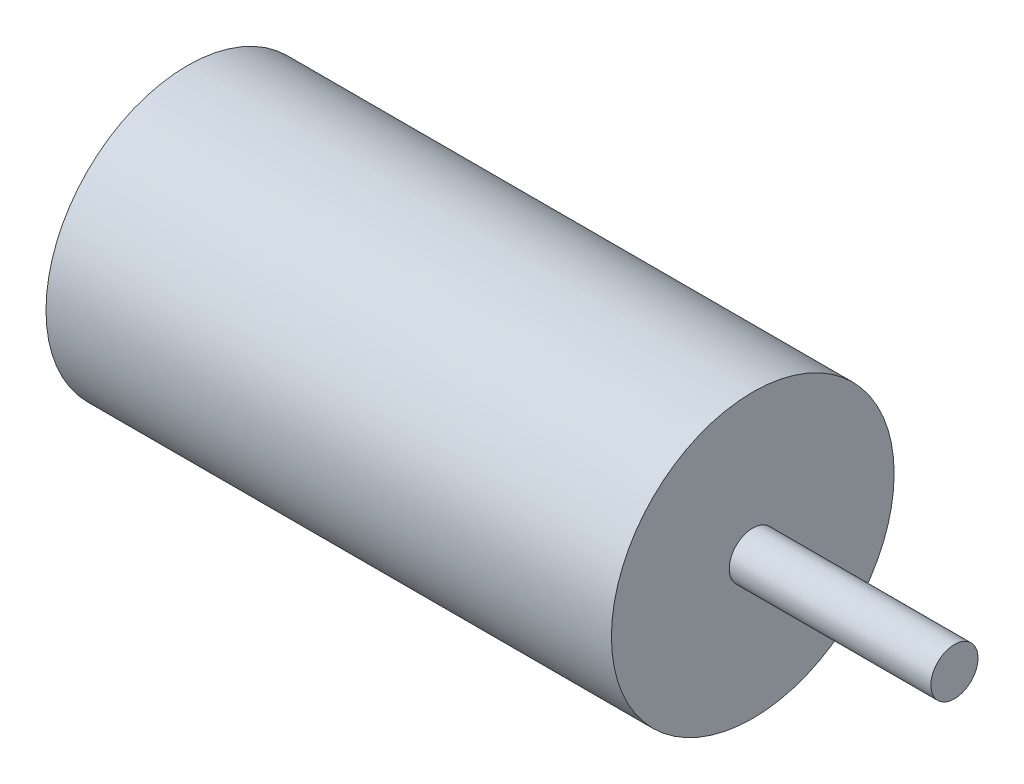
SolidWorks part; units mm, degrees
ref_plane "Front Plane" through (0, 0, 0) normal (0, 0, 1) x (1, 0, 0)
ref_plane "Top Plane" through (0, 0, 0) normal (0, 1, 0) x (1, 0, 0)
ref_plane "Right Plane" through (0, 0, 0) normal (1, 0, 0) x (0, 0, -1)
sketch "Sketch1" plane through (0, 0, 0) normal (1, 0, 0) x (0, 0, -1)
  circle A0 centre (0, 0) radius 19.05
  dimension "D1" = 38.1
extrude "Boss-Extrude1" add sketch "Sketch1" along normal blind 76.2
sketch "Sketch2" plane through (76.2, 0, 0) normal (1, 0, 0) x (0, 0, -1)
  circle A0 centre (0, 0) radius 3.175
  dimension "D1" = 6.35
extrude "Boss-Extrude2" add sketch "Sketch2" along normal blind 27.178
